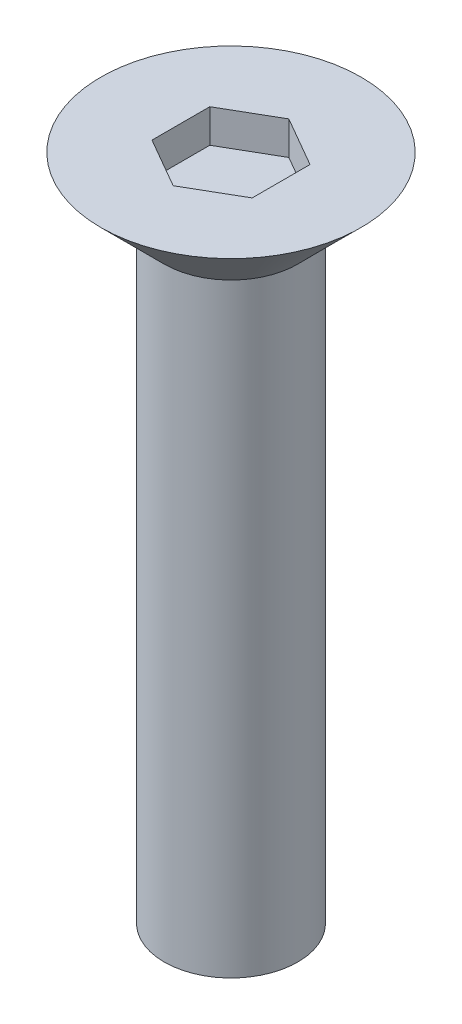
SolidWorks part; units mm, degrees
ref_plane "Front Plane" through (0, 0, 0) normal (0, 0, 1) x (1, 0, 0)
ref_plane "Top Plane" through (0, 0, 0) normal (0, 1, 0) x (1, 0, 0)
ref_plane "Right Plane" through (0, 0, 0) normal (1, 0, 0) x (0, 0, -1)
sketch "Sketch1" plane through (0, 0, 0) normal (0, 1, 0) x (1, 0, 0)
  circle A0 centre (0, 0) radius 2
  dimension "D1" = 4
extrude "Boss-Extrude1" add sketch "Sketch1" along normal blind 20
sketch "Sketch3" plane through (0, 0, 0) normal (1, 0, 0) x (0, 0, -1)
  line L0 (0, 20) -> (3.9, 20)
  line L1 (2, 20) -> (-2, 20) construction
  line L2 (3.9, 20) -> (0, 16.1)
  line L3 (0, 16.1) -> (0, 20)
  dimension "D1" = 3.9
  dimension "D2" = 45
revolve "Revolve1" add sketch "Sketch3" angle 360 about L3
sketch "Sketch4" plane through (0, 20, 0) normal (0, 1, 0) x (1, 0, 0)
  line L1 (0, 1.7321) -> (-1.5, 0.866)
  line L2 (-1.5, 0.866) -> (-1.5, -0.866)
  line L3 (-1.5, -0.866) -> (0, -1.7321)
  line L4 (0, -1.7321) -> (1.5, -0.866)
  line L5 (1.5, -0.866) -> (1.5, 0.866)
  line L6 (1.5, 0.866) -> (0, 1.7321)
  circle A0 centre (0, 0) radius 1.5 construction
  dimension "D1" = 3
extrude "Cut-Extrude1" cut sketch "Sketch4" against normal blind 1
